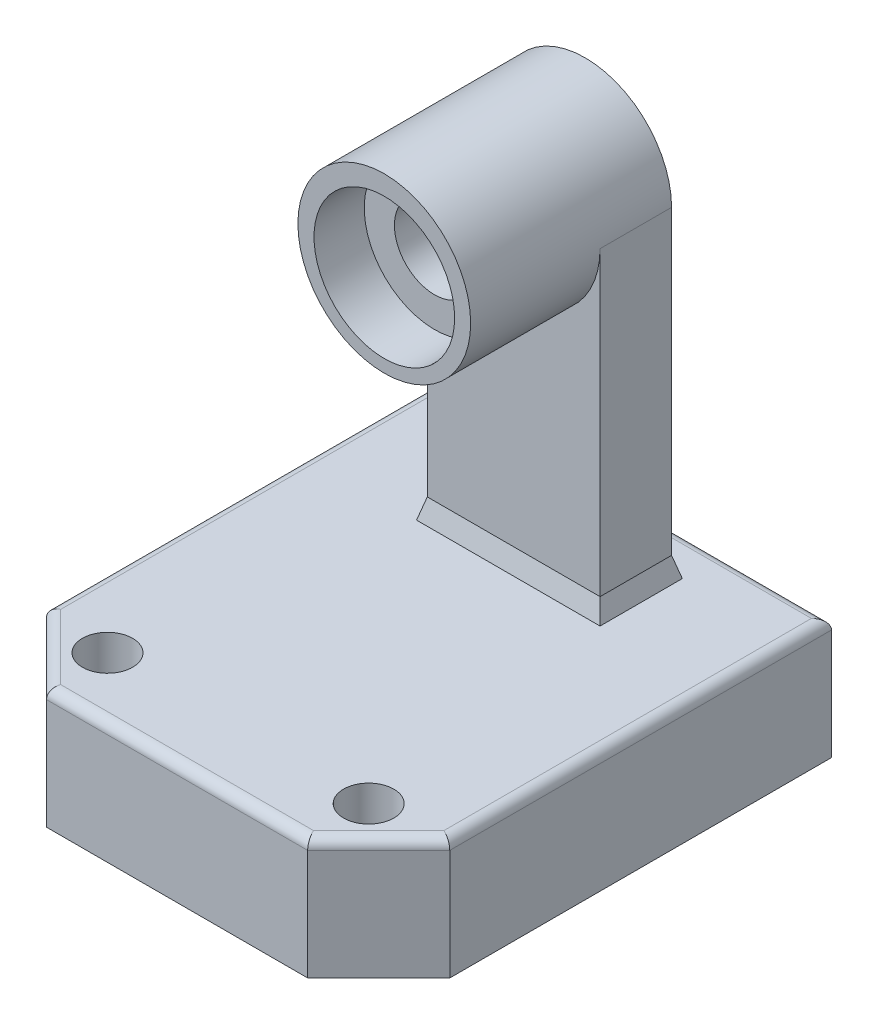
SolidWorks part; units mm, degrees
ref_plane "Front Plane" through (0, 0, 0) normal (0, 0, 1) x (1, 0, 0)
ref_plane "Top Plane" through (0, 0, 0) normal (0, 1, 0) x (1, 0, 0)
ref_plane "Right Plane" through (0, 0, 0) normal (1, 0, 0) x (0, 0, -1)
sketch "Sketch1" plane through (0, 0, 0) normal (0, 1, 0) x (1, 0, 0)
  line L0 (0, -38) -> (7.0711, -45.0711)
  line L1 (0, 0) -> (40.1421, 0)
  line L2 (0, 0) -> (0, -38)
  line L4 (40.1421, 0) -> (40.1421, -38)
  line L5 (7.0711, -45.0711) -> (33.0711, -45.0711)
  line L6 (33.0711, -45.0711) -> (40.1421, -38)
  line L7 (20.0711, 0) -> (20.0711, -45.0711) construction
  circle A0 centre (7.0711, -38) radius 2.5
  circle A1 centre (33.0711, -38) radius 2.5
  dimension "D4" = 5
  dimension "D6" = 5
  dimension "D1" = 38
  dimension "D2" = 10
  dimension "D3" = 10
  dimension "D5" = 26
  dimension "D7" = 26
  dimension "D8" = 38
  dimension "D9" = 13
extrude "Boss-Extrude1" add sketch "Sketch1" along normal blind 12 contours L0 L5 L6 L4 L1 L2
fillet "Fillet1" radius 1 6 edges at (20.0711, 12, 0) (40.1421, 12, 19) (36.6066, 12, 41.5355) (20.0711, 12, 45.0711) (3.5355, 12, 41.5355) (0, 12, 19)
sketch "Sketch2" plane through (0, 12, 0) normal (0, 1, 0) x (1, 0, 0)
  line L0 (20.0711, -1) -> (20.0711, -44.0711) construction
  line L1 (39.1421, -1) -> (1, -1) construction
  line L2 (7.4853, -44.0711) -> (32.6569, -44.0711) construction
  line L4 (11.0153, -3.9908) -> (29.2844, -3.9908)
  line L5 (11.0153, -3.9908) -> (11.0153, -12.1804)
  line L6 (11.0153, -12.1804) -> (29.2844, -12.1804)
  line L7 (29.2844, -3.9908) -> (29.2844, -12.1804)
extrude "Boss-Extrude2" add sketch "Sketch2" along normal blind 2 draft 15 contours L5 L4 L7 L6
sketch "Sketch4" plane through (0, 14, 0) normal (0, 1, 0) x (1, 0, 0)
  line L1 (11.5512, -4.5267) -> (28.7485, -4.5267)
  line L2 (11.5512, -4.5267) -> (11.5512, -11.6445)
  line L3 (11.5512, -11.6445) -> (28.7485, -11.6445)
  line L4 (28.7485, -4.5267) -> (28.7485, -11.6445)
extrude "Boss-Extrude3" add sketch "Sketch4" along normal blind 30
sketch "Sketch5" plane through (0, 12, 0) normal (0, 1, 0) x (1, 0, 0)
  line L0 (39.1421, -1) -> (1, -1) construction
  line L1 (20.0711, -1) -> (20.0711, -44.0711) construction
  line L2 (7.4853, -44.0711) -> (32.6569, -44.0711) construction
  circle A0 centre (33.0711, -39) radius 2.5
  circle A1 centre (7.0711, -39) radius 2.5
  dimension "D2" = 5
  dimension "D3" = 5
  dimension "D1" = 26
  dimension "D4" = 38
  dimension "D5" = 13
extrude "Cut-Extrude1" cut sketch "Sketch5" against normal blind 8
sketch "Sketch6" plane through (0, 0, 4.5267) normal (0, 0, -1) x (-1, 0, 0)
  line L0 (-28.7485, 44) -> (-11.5512, 44) construction
  circle A0 centre (-20.1498, 44) radius 8.5987
extrude "Boss-Extrude4" add sketch "Sketch6" against normal blind 20
sketch "Sketch7" plane through (0, 0, 24.5267) normal (0, 0, 1) x (1, 0, 0)
  circle A0 centre (20.1552, 43.6668) radius 7
  circle A1 centre (20.1552, 43.6668) radius 3.9989
extrude "Cut-Extrude2" cut sketch "Sketch7" against normal blind 5
sketch "Sketch8" plane through (0, 0, 24.5267) normal (0, 0, 1) x (1, 0, 0)
  circle A0 centre (20.1552, 43.6668) radius 3.9989
extrude "Cut-Extrude3" cut sketch "Sketch8" against normal through all
